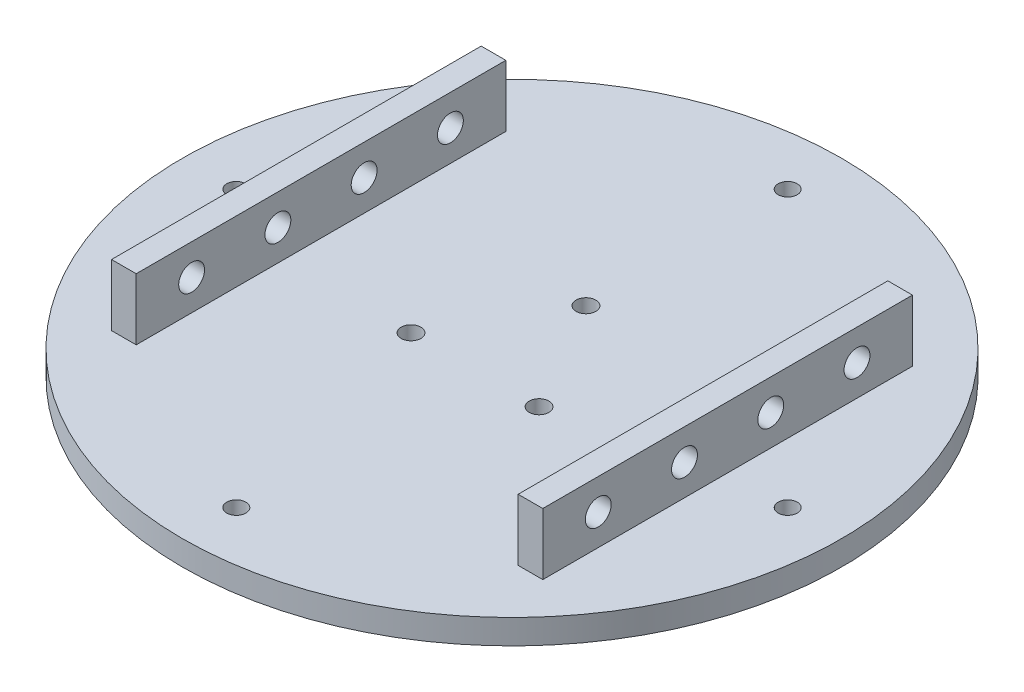
SolidWorks part; units mm, degrees
ref_plane "前视基准面" through (0, 0, 0) normal (0, 0, 1) x (1, 0, 0)
ref_plane "上视基准面" through (0, 0, 0) normal (0, 1, 0) x (1, 0, 0)
ref_plane "右视基准面" through (0, 0, 0) normal (1, 0, 0) x (0, 0, -1)
sketch "草图1" plane through (0, 0, 0) normal (0, 1, 0) x (1, 0, 0)
  line L0 (-101.6017, 0) -> (88.2468, 0) construction
  line L1 (0, 82.4859) -> (0, -88.2468) construction
  line L2 (0, 0) -> (87.6019, -50.577) construction
  line L3 (0, 0) -> (-78.6573, -45.4128) construction
  circle A0 centre (0, 0) radius 53.4919
  circle A1 centre (0, 44.75) radius 1.55
  circle A2 centre (-44.75, 0) radius 1.55
  circle A3 centre (44.75, 0) radius 1.55
  circle A4 centre (0, -44.75) radius 1.55
  circle A5 centre (0, 0) radius 12 construction
  circle A6 centre (0, 12) radius 1.6
  circle A7 centre (10.3923, -6) radius 1.6
  circle A8 centre (-10.3923, -6) radius 1.6
  dimension "D1" = 89.5
  dimension "D3" = 3.1
  dimension "D4" = 3.1
  dimension "D7" = 3.2
  dimension "D2" = 89.5
  dimension "D5" = 120
  dimension "D6" = 120
extrude "云台基座" add sketch "草图1" along normal blind 4
sketch "草图2" plane through (0, 4, 0) normal (0, 1, 0) x (1, 0, 0)
  line L0 (-75.36, 0) -> (112.2315, 0) construction
  line L1 (0, 57.086) -> (0, -62.5844) construction
  line L2 (-35, 45.9881) -> (-35, -61.2176) construction
  line L3 (35, 30) -> (31, 30)
  line L4 (-35, 30) -> (-31, 30)
  line L5 (-35, 30) -> (-35, -30)
  line L6 (-35, -30) -> (-31, -30)
  line L7 (-31, 30) -> (-31, -30)
  line L8 (35, -30) -> (31, -30)
  line L9 (35, 30) -> (35, -30)
  line L10 (31, 30) -> (31, -30)
  point P11 (0, 0)
  dimension "D1" = 31
  dimension "D2" = 4
  dimension "D3" = 60
extrude "设计平台支架" add sketch "草图2" along normal blind 10
sketch "草图3" plane through (-35, 0, 0) normal (-1, 0, 0) x (0, 0, 1)
  line L0 (-49.8602, 9) -> (38.8694, 9) construction
  line L1 (0, -15.3684) -> (0, 30.3681) construction
  line L2 (-30, 14) -> (-30, 4) construction
  circle A0 centre (7, 9) radius 2.1
  circle A1 centre (-7, 9) radius 2.1
  circle A2 centre (-21, 9) radius 2.1
  circle A3 centre (21, 9) radius 2.1
  point P7 (-30, 9)
  dimension "D1" = 4.2
  dimension "D2" = 4.2
  dimension "D3" = 7
  dimension "D4" = 14
  dimension "D5" = 9
extrude "射击平台支架安装孔" cut sketch "草图3" against normal through all
